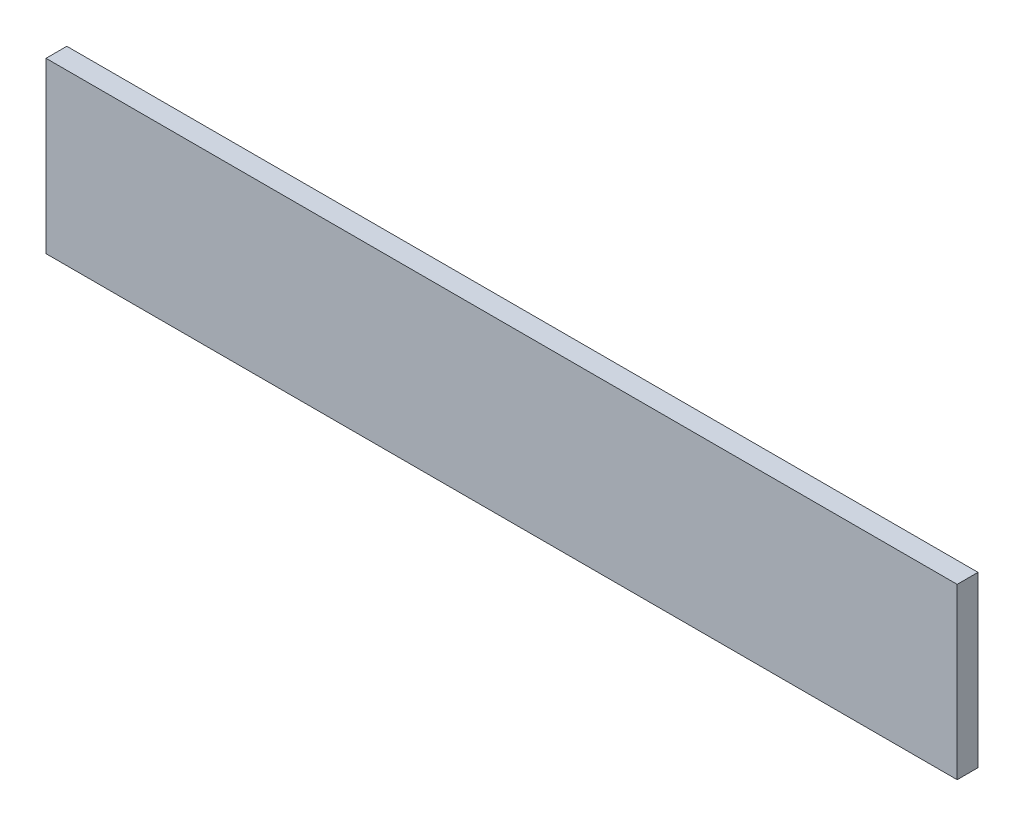
SolidWorks part; units mm, degrees
material "Custom Plastic"
ref_plane "X-Y Datum" through (0, 0, 0) normal (0, 0, 1) x (1, 0, 0)
ref_plane "X-Z Datum" through (0, 0, 0) normal (0, 1, 0) x (1, 0, 0)
ref_plane "Y-Z Datum" through (0, 0, 0) normal (1, 0, 0) x (0, 0, -1)
sketch "Sketch1" plane through (0, 0, 0) normal (0, 0, 1) x (1, 0, 0)
  line L1 (-35, -6.5) -> (35, -6.5)
  line L2 (-35, -6.5) -> (-35, 6.5)
  line L3 (-35, 6.5) -> (35, 6.5)
  line L4 (35, -6.5) -> (35, 6.5)
  line L5 (-35, -6.5) -> (35, 6.5) construction
  line L6 (-35, 6.5) -> (35, -6.5) construction
  point P0 (0, 0)
  dimension "D1" = 70
  dimension "D2" = 13
extrude "Boss-Extrude1" add sketch "Sketch1" along normal blind 1.6
